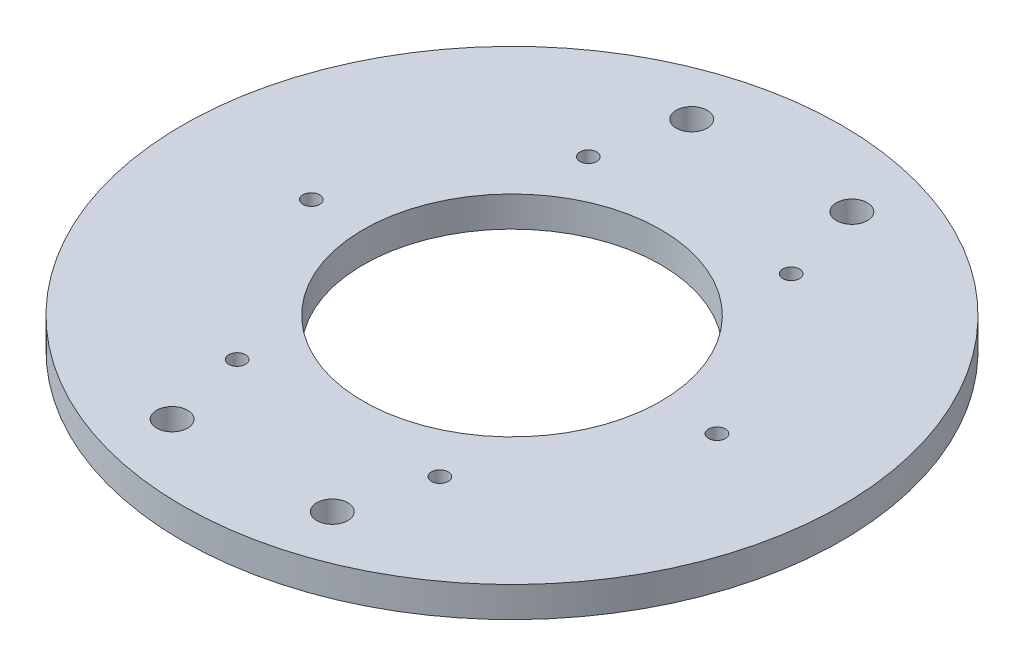
SolidWorks part; units mm, degrees
ref_plane "Front Plane" through (0, 0, 0) normal (0, 0, 1) x (1, 0, 0)
ref_plane "Top Plane" through (0, 0, 0) normal (0, 1, 0) x (1, 0, 0)
ref_plane "Right Plane" through (0, 0, 0) normal (1, 0, 0) x (0, 0, -1)
sketch "Sketch1" plane through (0, 0, 0) normal (0, 1, 0) x (1, 0, 0)
  circle A0 centre (0, 0) radius 18.6309
  circle A1 centre (0, 0) radius 41.275
  dimension "D1" = 37.2618
  dimension "D2" = 82.55
extrude "Boss-Extrude1" add sketch "Sketch1" along normal blind 3.81
sketch "Sketch3" plane through (0, 0, 0) normal (0, -1, 0) x (1, 0, 0)
  circle A0 centre (12.9673, 21.997) radius 1.0493
  circle A1 centre (-12.4327, 21.997) radius 1.0493
  circle A2 centre (-25.1327, 0) radius 1.0493
  circle A3 centre (-12.4327, -21.997) radius 1.0493
  circle A4 centre (12.9673, -21.997) radius 1.0493
  circle A5 centre (25.6673, 0) radius 1.0493
  dimension "D1" = 2.0985
  dimension "D2" = 2.0985
  dimension "D3" = 2.0985
  dimension "D4" = 2.0985
  dimension "D5" = 2.0985
  dimension "D6" = 2.0985
extrude "Cut-Extrude1" cut sketch "Sketch3" against normal through all both and the other way through all
sketch "Sketch4" plane through (0, 3.81, 0) normal (0, 1, 0) x (1, 0, 0)
  circle A0 centre (-10.0315, 32.5374) radius 1.9431
  circle A1 centre (-10.0315, -32.5374) radius 1.9431
  circle A2 centre (10.0315, -32.5374) radius 1.9431
  circle A3 centre (10.0315, 32.5374) radius 1.9431
  dimension "D1" = 3.8862
  dimension "D2" = 3.8862
  dimension "D3" = 3.8862
  dimension "D4" = 3.8862
  dimension "D5" = 34.0487
  dimension "D6" = 34.0487
  dimension "D7" = 34.0487
  dimension "D8" = 34.0487
  dimension "D9" = 65.0748
  dimension "D10" = 65.0748
  dimension "D11" = 0
  dimension "D12" = 0
extrude "Cut-Extrude2" cut sketch "Sketch4" against normal through all both and the other way through all
